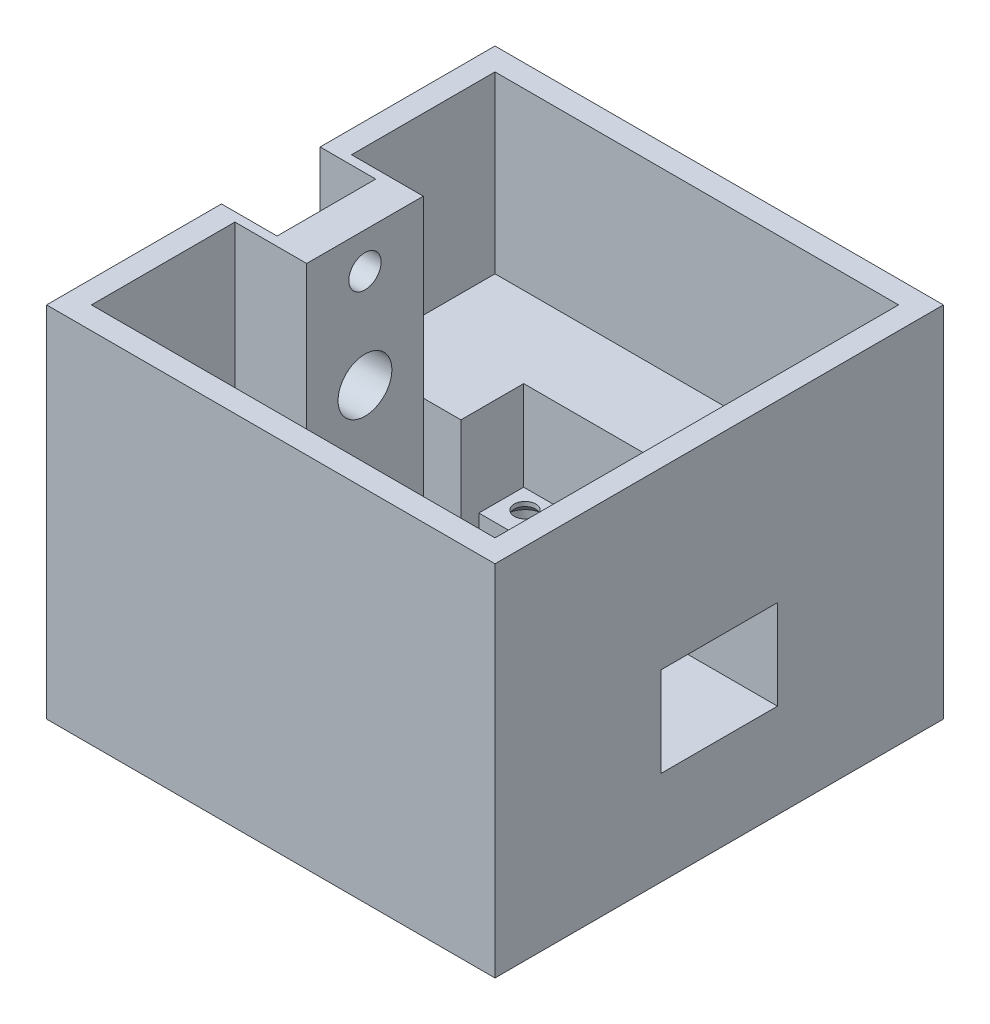
SolidWorks part; units mm, degrees
ref_plane "Front Plane" through (0, 0, 0) normal (0, 0, 1) x (1, 0, 0)
ref_plane "Top Plane" through (0, 0, 0) normal (0, 1, 0) x (1, 0, 0)
ref_plane "Right Plane" through (0, 0, 0) normal (1, 0, 0) x (0, 0, -1)
sketch "Sketch1" plane through (0, 0, 0) normal (0, 1, 0) x (1, 0, 0)
  line L1 (25, 25) -> (-25, 25)
  line L2 (25, 25) -> (25, -25)
  line L3 (25, -25) -> (-25, -25)
  line L4 (-25, 25) -> (-25, -25)
  line L5 (25, 25) -> (-25, -25) construction
  line L6 (25, -25) -> (-25, 25) construction
  point P0 (0, 0)
  dimension "D1" = 50
  dimension "D2" = 50
extrude "Boss-Extrude1" add sketch "Sketch1" along normal blind 40
shell "Shell1" thickness 2.5
sketch "Sketch2" plane through (0, 2.5, 0) normal (0, 1, 0) x (1, 0, 0)
  line L0 (9.676, 18.6496) -> (-10.324, 18.6496) construction
  line L1 (9.676, 18.6496) -> (9.676, -15.3504) construction
  line L2 (-10.3, -15.3504) -> (-10.324, -15.3504) construction
  line L3 (-10.324, 18.6496) -> (-10.324, -15.3504) construction
  line L4 (-10.3, 4.5) -> (-22.5, 4.5)
  line L5 (-22.5, 4.5) -> (-22.5, 22.5)
  line L6 (-22.5, 22.5) -> (0, 22.5)
  line L7 (-10.3, 4.5) -> (-10.3, 13.5)
  line L8 (-10.3, 13.5) -> (0, 13.5)
  line L9 (22.5, 4.5) -> (22.5, 22.5)
  line L10 (10.3, 4.5) -> (22.5, 4.5)
  line L11 (10.3, 4.5) -> (10.3, 13.5)
  line L12 (10.3, 13.5) -> (0, 13.5)
  line L13 (22.5, 22.5) -> (0, 22.5)
  line L14 (10.3, -12) -> (22.5, -12)
  line L15 (12.1528, -14.5584) -> (12.1503, -21.7784) construction
  line L16 (-22.5, -12) -> (-22.5, -22.5)
  line L17 (-10.3, -12) -> (-22.5, -12)
  line L18 (-10.3, -12) -> (-10.3, -19.19)
  line L19 (-10.3, -19.19) -> (0.1901, -19.19)
  line L20 (-22.5, -22.5) -> (2.3162, -22.5)
  line L21 (-10.324, 18.6496) -> (-10.324, 11.4396) construction
  line L22 (10.3, -12) -> (10.3, -19.19)
  line L23 (9.676, -15.3504) -> (-10.3, -15.3504) construction
  line L24 (10.3, -19.19) -> (0.1901, -19.19)
  line L25 (22.5, -22.5) -> (2.3162, -22.5)
  line L26 (22.5, -12) -> (22.5, -22.5)
  line L27 (-22.5, -22.5) -> (22.5, -22.5) construction
  line L28 (-22.5, 22.5) -> (-22.5, -22.5) construction
  line L29 (-22.5, 22.5) -> (-22.5, -22.5) construction
  line L30 (22.5, 22.5) -> (-22.5, 22.5) construction
  point P0 (2.1262, -4.7549)
  dimension "D1" = 18
  dimension "D2" = 10.5
  dimension "D3" = 9
extrude "Boss-Extrude2" [suppressed] add sketch "Sketch2" along normal blind 18
sketch "Sketch4" [suppressed] plane through (0, 2.5, 0) normal (0, 1, 0) x (1, 0, 0)
  line L0 (22.5, -12) -> (22.5, 4.5)
  line L1 (22.5, -3.75) -> (15.5, -3.75)
  line L3 (14, -2.25) -> (17, -2.25)
  line L4 (14, -2.25) -> (14, -5.25)
  line L5 (14, -5.25) -> (17, -5.25)
  line L6 (17, -2.25) -> (17, -5.25)
  line L7 (14, -2.25) -> (17, -5.25) construction
  line L8 (14, -5.25) -> (17, -2.25) construction
  dimension "D1" = 3
  dimension "D2" = 3
  dimension "D3" = 7
extrude "Cut-Extrude2" [suppressed] cut sketch "Sketch4" against normal through all
sketch "Sketch5" [suppressed] plane through (-22.5, 0, 0) normal (1, 0, 0) x (0, 0, -1)
  line L0 (4.5, 2.5) -> (-12, 2.5) construction
  line L1 (-6.75, 2.5) -> (-0.75, 2.5)
  line L2 (-6.75, 2.5) -> (-6.75, 40)
  line L3 (-6.75, 40) -> (-0.75, 40)
  line L4 (-0.75, 2.5) -> (-0.75, 40)
  line L5 (22.5, 40) -> (-22.5, 40) construction
  line L6 (-12, 2.5) -> (4.5, 2.5) construction
  point P12 (-3.75, 2.5)
  point P16 (-3.75, 2.5)
  dimension "D1" = 6
extrude "Boss-Extrude3" [suppressed] add sketch "Sketch5" along normal blind 2.5
sketch "Sketch6" [suppressed] plane through (-20, 0, 0) normal (1, 0, 0) x (0, 0, -1)
  line L0 (-6.75, 21.25) -> (-0.75, 21.25)
  line L1 (-6.75, 40) -> (-6.75, 2.5) construction
  line L2 (-0.75, 2.5) -> (-0.75, 40) construction
  line L4 (-5.5999, 21.4224) -> (-3.4786, 23.5437)
  line L5 (-5.5999, 21.4224) -> (-3.4786, 19.3011)
  line L6 (-3.4786, 19.3011) -> (-1.3573, 21.4224)
  line L7 (-3.4786, 23.5437) -> (-1.3573, 21.4224)
  line L8 (-5.2251, 22.5516) -> (-2.05, 19.75) construction
  line L9 (-5.05, 19.75) -> (-2.2784, 22.948) construction
  point P6 (-3.75, 21.25)
  dimension "D1" = 3
  dimension "D2" = 3
extrude "Cut-Extrude3" [suppressed] cut sketch "Sketch6" against normal through all contours L5 L6 L0 | L7 L4 L5 L0 L6
hole_wizard "M1.6 Tapped Hole1" [suppressed] positions "Sketch7" profile "Sketch8" tap size "M1.6" standard "ISO"
sketch "Sketch7" [suppressed] plane through (0, 12.5, 0) normal (0, 1, 0) x (1, 0, 0)
  line L0 (-10.3, 4.5) -> (-10.3, 11.5) construction
  line L1 (-22.5, 4.5) -> (-10.3, 4.5) construction
  line L2 (22.5, -12) -> (10.3, -12) construction
  line L3 (10.3, -12) -> (10.3, -19.19) construction
  point P0 (-12.3, 6.5)
  point P2 (12.3, -14)
  dimension "D1" = 2
  dimension "D2" = 2
  dimension "D3" = 2
  dimension "D4" = 2
sketch "Sketch8" plane through (-12.3, 12.5, -6.5) normal (1, 0, 0) x (0, 0, 1)
  line L0 (0, 0) -> (0, 12.5)
  line L1 (0, 12.5) -> (0.625, 12.5)
  line L2 (0.625, 12.5) -> (0.625, 0.2)
  line L3 (0.625, 0.2) -> (0.825, 0)
  line L5 (0.825, 0) -> (0, 0)
  line L6 (-0.625, 0.2) -> (-0.825, 0) construction
  line L11 (0, -6.35) -> (0, 107.95) construction
  dimension "Thru Tap Drill Dia." = 1.25
  dimension "Thru Tap Drill Depth" = 12.5
  dimension "Near C'Sink Dia." = 1.65
  dimension "Near C'Sink Angle" = 90
cosmetic thread "Hole Thread1" [suppressed] parameters "D2"=1.6
cosmetic thread "Hole Thread2" [suppressed] parameters "D2"=1.6
sketch "Sketch9" [suppressed] plane through (0, 2.5, 0) normal (0, 1, 0) x (1, 0, 0)
  line L1 (-10.3, 13.5) -> (10.3, 13.5)
  line L2 (-10.3, 13.5) -> (-10.3, -19.19)
  line L3 (-10.3, -19.19) -> (10.3, -19.19)
  line L4 (10.3, 13.5) -> (10.3, -19.19)
extrude "Boss-Extrude4" [suppressed] add sketch "Sketch9" along normal blind 8
hole_wizard "CSK SLOT for M1.6 Countersunk Flat Head Screw1" [suppressed] positions "Sketch10" profile "Sketch11" size "M1.6" standard "ISO"
sketch "Sketch10" [suppressed] plane through (0, 10.5, 0) normal (0, 1, 0) x (1, 0, 0)
  line L0 (0, 0) -> (0, 4.5)
  point P0 (0, 4.5)
  dimension "D1" = 4.5
sketch "Sketch11" plane through (0, 10.5, -4.5) normal (1, 0, 0) x (0, 0, 1)
  line L0 (0, 0) -> (0, 10.5)
  line L1 (0, 10.5) -> (0.9, 10.5)
  line L2 (0.9, 10.5) -> (0.9, 6.9)
  line L3 (0.9, 6.9) -> (1.8, 6)
  line L4 (1.8, 6) -> (1.8, 0)
  line L6 (1.8, 0) -> (0, 0)
  line L7 (-0.9, 6.9) -> (-1.8, 6) construction
  line L11 (0, -6.35) -> (0, 107.95) construction
  dimension "Thru Hole Dia." = 1.8
  dimension "Thru Hole Depth" = 10.5
  dimension "C'Sink Dia." = 3.6
  dimension "C'Sink Angle" = 90
  dimension "Head Clearance" = 6
ref_plane "Plane1" [suppressed] through (0, 10.5, 0) normal (0, 1, 0) x (1, 0, 0)
sketch "Sketch12" [suppressed] plane through (0, 10.5, 0) normal (0, 1, 0) x (1, 0, 0)
  line L0 (0, 22.5) -> (0, -22.5)
  line L1 (22.5, 22.5) -> (-22.5, 22.5) construction
  line L2 (-22.5, -22.5) -> (22.5, -22.5) construction
  point P6 (0, -11)
  point P7 (0, 11)
  point P8 (0, 0)
  dimension "D1" = 11
  dimension "D2" = 11
hole_wizard "CSK SLOT for M1.6 Countersunk Flat Head Screw2" [suppressed] positions "Sketch13" profile "Sketch14" size "M1.6" standard "ISO"
sketch "Sketch13" [suppressed] plane through (0, 10.5, 0) normal (0, 1, 0) x (1, 0, 0)
  point P0 (0, -11)
  point P3 (0, 11)
sketch "Sketch14" plane through (0, 10.5, 11) normal (1, 0, 0) x (0, 0, 1)
  line L0 (0, 0) -> (0, 10.5)
  line L1 (0, 10.5) -> (0.9, 10.5)
  line L2 (0.9, 10.5) -> (0.9, 7.9)
  line L3 (0.9, 7.9) -> (1.8, 7)
  line L4 (1.8, 7) -> (1.8, 0)
  line L6 (1.8, 0) -> (0, 0)
  line L7 (-0.9, 7.9) -> (-1.8, 7) construction
  line L11 (0, -6.35) -> (0, 107.95) construction
  dimension "Thru Hole Dia." = 1.8
  dimension "Thru Hole Depth" = 10.5
  dimension "C'Sink Dia." = 3.6
  dimension "C'Sink Angle" = 90
  dimension "Head Clearance" = 7
sketch "Sketch15" [suppressed] plane through (0, 0, 0) normal (0, -1, 0) x (1, 0, 0)
  line L0 (-25, 0) -> (25, 0)
  line L1 (-25, -25) -> (-25, 25) construction
  line L2 (25, 25) -> (25, -25) construction
  line L3 (0, -22.5) -> (0, 22.5) construction
  line L4 (-4.5, 15.5) -> (4.5, 15.5)
  line L5 (-4.5, 15.5) -> (-4.5, -15.5)
  line L6 (-4.5, -15.5) -> (4.5, -15.5)
  line L7 (4.5, 15.5) -> (4.5, -15.5)
  line L8 (-4.5, 15.5) -> (4.5, -15.5) construction
  line L9 (-4.5, -15.5) -> (4.5, 15.5) construction
  point P6 (0, 0)
  point P8 (0, 0)
  dimension "D1" = 31
  dimension "D2" = 9
extrude "Cut-Extrude4" [suppressed] cut sketch "Sketch15" against normal blind 6.1 contours L5 L6 L7 L4
sketch "Sketch16" plane through (0, 2.5, 0) normal (0, 1, 0) x (1, 0, 0)
  line L0 (9.676, 17.0496) -> (-10.324, 17.0496) construction
  line L1 (9.676, 17.0496) -> (9.676, -16.9504) construction
  line L2 (-10.3, -16.9504) -> (-10.324, -16.9504) construction
  line L3 (-10.324, 17.0496) -> (-10.324, -16.9504) construction
  line L4 (-10.3, 6.5) -> (-22.5, 6.5)
  line L5 (-22.5, 6.5) -> (-22.5, 22.5)
  line L6 (-22.5, 22.5) -> (-5.1691, 22.5)
  line L7 (-10.3, 6.5) -> (-10.3, 13.5)
  line L8 (-10.3, 13.5) -> (-5.1691, 13.5)
  line L9 (22.5, 6.5) -> (22.5, 22.5)
  line L10 (10.3, 6.5) -> (22.5, 6.5)
  line L11 (10.3, 6.5) -> (10.3, 13.5)
  line L12 (10.3, 13.5) -> (-5.1691, 13.5)
  line L13 (22.5, 22.5) -> (-5.1691, 22.5)
  line L14 (10.3, -13.6) -> (22.5, -13.6)
  line L15 (4.8575, -15.2543) -> (4.855, -22.4742) construction
  line L16 (-22.5, -13.6) -> (-22.5, -22.5)
  line L17 (-10.3, -13.6) -> (-22.5, -13.6)
  line L18 (-10.3, -13.6) -> (-10.3, -20.79)
  line L19 (-10.3, -20.79) -> (-4.9791, -20.79)
  line L20 (-22.5, -22.5) -> (-4.9791, -22.5)
  line L21 (-10.324, 17.0496) -> (-10.324, 9.8396) construction
  line L22 (10.3, -13.6) -> (10.3, -20.79)
  line L23 (9.676, -16.9504) -> (-10.3, -16.9504) construction
  line L24 (10.3, -20.79) -> (-4.9791, -20.79)
  line L25 (22.5, -22.5) -> (-4.9791, -22.5)
  line L26 (22.5, -13.6) -> (22.5, -22.5)
  line L27 (22.5, 22.5) -> (-22.5, 22.5) construction
  line L29 (22.5, -22.5) -> (22.5, 22.5) construction
  line L30 (22.5, -22.5) -> (22.5, 22.5) construction
  line L31 (-22.5, -22.5) -> (22.5, -22.5) construction
  point P0 (-5.1691, -5.4508)
  dimension "D1" = 34
  dimension "D2" = 12.2
  dimension "D3" = 16
  dimension "D4" = 8.9
  dimension "D5" = 1.71
  dimension "D6" = 12.2
  dimension "D7" = 9
  dimension "D8" = 45
  dimension "D9" = 45
extrude "Boss-Extrude5" add sketch "Sketch16" along normal blind 18
sketch "Sketch17" plane through (0, 2.5, 0) normal (0, 1, 0) x (1, 0, 0)
  line L1 (0, 22.5) -> (0, -22.5)
  line L2 (22.5, 22.5) -> (-22.5, 22.5) construction
  line L3 (-22.5, -22.5) -> (22.5, -22.5) construction
  line L4 (0, 0) -> (-22.5, 0)
  line L5 (-22.5, 6.5) -> (-22.5, -13.6) construction
  line L6 (-22.5, 22.5) -> (-22.5, -22.5) construction
  line L7 (22.5, 6.5) -> (-22.5, 6.5)
  line L8 (22.5, 6.5) -> (22.5, -6.5)
  line L9 (22.5, -6.5) -> (-22.5, -6.5)
  line L10 (-22.5, 6.5) -> (-22.5, -6.5)
  line L11 (22.5, 6.5) -> (-22.5, -6.5) construction
  line L12 (22.5, -6.5) -> (-22.5, 6.5) construction
  line L13 (-22.5, 6.5) -> (-10.3, 6.5) construction
  line M11 (22.5, -13.6) -> (22.5, 6.5)
  line M12 (22.5, 6.5) -> (10.3, 6.5)
  line M16 (-10.3, 6.5) -> (-22.5, 6.5)
  line M17 (-22.5, 6.5) -> (-22.5, -13.6)
extrude "Boss-Extrude6" add sketch "Sketch17" along normal blind 8 contours L1 L7 L4 M16 M17 | L9 L1 L4 M17 | L9 L7 L1 M11 M12
sketch "Sketch18" plane through (-22.5, 0, 0) normal (1, 0, 0) x (0, 0, -1)
  line L0 (-22.5, 40) -> (22.5, 40)
  line L1 (22.5, 40) -> (0, 40)
  line L2 (0, 40) -> (0, 10.5)
  line L3 (6.5, 10.5) -> (-6.5, 10.5) construction
  line L5 (6.5, 40) -> (-6.5, 40)
  line L6 (6.5, 40) -> (6.5, 10.5)
  line L7 (6.5, 10.5) -> (-6.5, 10.5)
  line L8 (-6.5, 40) -> (-6.5, 10.5)
  line L9 (6.5, 40) -> (-6.5, 10.5) construction
  line L10 (6.5, 10.5) -> (-6.5, 40) construction
  point P9 (0, 25.25)
  line M2 (-6.5, 10.5) -> (6.5, 10.5)
  line M3 (6.5, 10.5) -> (6.5, 20.5)
extrude "Boss-Extrude7" add sketch "Sketch18" along normal blind 8 contours L6 L1 L2 M2 M3 | L0 L8 L2 M2
sketch "Sketch19" plane through (-25, 0, 0) normal (-1, 0, 0) x (0, 0, 1)
  line L0 (-25, 40) -> (25, 40) construction
  line L2 (0, 9.8) -> (0, 0) construction
  line L3 (-5.5, 9.8) -> (5.5, 9.8)
  line L4 (-5.5, 9.8) -> (-5.5, 40)
  line L5 (-5.5, 40) -> (5.5, 40)
  line L6 (5.5, 9.8) -> (5.5, 40)
  point P5 (0, 20)
  point P7 (0, 20)
  dimension "D1" = 30.2
  dimension "D2" = 11
extrude "Cut-Extrude5" cut sketch "Sketch19" against normal blind 6.2
sketch "Sketch20" plane through (0, 0, 0) normal (0, -1, 0) x (1, 0, 0)
  line L0 (-25, 0) -> (25, 0)
  line L1 (-25, -25) -> (-25, 25) construction
  line L2 (25, 25) -> (25, -25) construction
  line L4 (15.1, 5.4) -> (-15.1, 5.4)
  line L5 (15.1, 5.4) -> (15.1, -5.4)
  line L6 (15.1, -5.4) -> (-15.1, -5.4)
  line L7 (-15.1, 5.4) -> (-15.1, -5.4)
  line L8 (15.1, 5.4) -> (-15.1, -5.4) construction
  line L9 (15.1, -5.4) -> (-15.1, 5.4) construction
  point P6 (0, 0)
  point P8 (0, 0)
  dimension "D1" = 30.2
  dimension "D2" = 10.8
extrude "Cut-Extrude6" cut sketch "Sketch20" against normal blind 6.2 contours L4 L7 L0 L5 | L0 L7 L6 L5
sketch "Sketch21" plane through (0, 2.5, 0) normal (0, 1, 0) x (1, 0, 0)
  line L0 (0, -20.79) -> (0, -11.8673) construction
  line L1 (10.3, -20.79) -> (5.3, -20.79)
  line L2 (10.3, -20.79) -> (10.3, -15.79)
  line L3 (10.3, -15.79) -> (5.3, -15.79)
  line L4 (5.3, -20.79) -> (5.3, -15.79)
  line L5 (10.3, -20.79) -> (-10.3, -20.79) construction
  line L6 (-10.3, -15.79) -> (-5.3, -15.79)
  line L7 (-5.3, -20.79) -> (-5.3, -15.79)
  line L8 (-10.3, -20.79) -> (-5.3, -20.79)
  line L9 (-10.3, -20.79) -> (-10.3, -15.79)
  dimension "D1" = 5
  dimension "D2" = 5
extrude "Boss-Extrude8" add sketch "Sketch21" along normal blind 8
sketch3d "3DSketch1"
  line L0 (-10.3, 10.5, 15.79) -> (-10.3, 10.5, 20.79) construction
  line L5 (-10.3, 10.5, 20.79) -> (-5.3, 10.5, 20.79) construction
  line L6 (10.3, 10.5, 20.79) -> (10.3, 10.5, 15.79) construction
  line L7 (5.3, 10.5, 20.79) -> (10.3, 10.5, 20.79) construction
  point P0 (-8, 10.5, 18.64)
  point P7 (8, 10.5, 18.64)
  dimension "D1" = 2.3
  dimension "D2" = 2.15
  dimension "D3" = 2.3
  dimension "D4" = 2.15
hole_wizard "CSK SLOT for M1.6 Countersunk Flat Head Screw3" [suppressed] positions "Sketch22" profile "Sketch23" size "M1.6" standard "ISO"
sketch "Sketch22" plane through (0, 0, 0) normal (0, -1, 0) x (-1, 0, 0)
  line L0 (25, -25) -> (-25, -25) construction
  line L1 (-25, -25) -> (-25, 25) construction
  line L2 (25, 25) -> (25, -25) construction
  line L3 (-25, 25) -> (25, 25) construction
  point P0 (-8, -18.64)
  point P3 (8, -18.64)
  point P19 (-8, 11.35)
  point P21 (8, 11.35)
  dimension "D1" = 6.36
  dimension "D2" = 17
  dimension "D3" = 17
  dimension "D4" = 6.36
  dimension "D5" = 17
  dimension "D6" = 17
  dimension "D7" = 13.65
  dimension "D8" = 13.65
sketch "Sketch23" plane through (8, 0, 18.64) normal (1, 0, 0) x (0, 0, -1)
  line L0 (0, 0) -> (0, 40)
  line L1 (0, 40) -> (0.9, 40)
  line L2 (0.9, 40) -> (0.9, 9.9)
  line L3 (0.9, 9.9) -> (1.8, 9)
  line L4 (1.8, 9) -> (1.8, 0)
  line L6 (1.8, 0) -> (0, 0)
  line L7 (-0.9, 9.9) -> (-1.8, 9) construction
  line L11 (0, -6.35) -> (0, 107.95) construction
  dimension "Thru Hole Dia." = 1.8
  dimension "Thru Hole Depth" = 40
  dimension "C'Sink Dia." = 3.6
  dimension "C'Sink Angle" = 90
  dimension "Head Clearance" = 9
ref_plane "Plane3" through (0, 0, 3.79) normal (0, 0, -1) x (-1, 0, 0)
mirror "Mirror1" [suppressed] about plane through (0, 0, 3.79) normal (0, 0, -1)
sketch "Sketch24" plane through (0, 10.5, 0) normal (0, 1, 0) x (1, 0, 0)
  line L0 (-25, 0) -> (25, 0) construction
  line L1 (-25, 5.5) -> (-25, -5.5) construction
  line L2 (25, -25) -> (25, 25) construction
  point P6 (-11, 0)
  point P7 (11, 0)
  point P8 (0, 0)
  dimension "D1" = 11
  dimension "D2" = 11
hole_wizard "CSK SLOT for M1.6 Countersunk Flat Head Screw4" positions "Sketch27" profile "Sketch26" size "M1.6" standard "ISO" slot yes end condition through all
sketch "Sketch27" plane through (0, 10.5, 0) normal (0, 1, 0) x (1, 0, 0)
  point P0 (-11, 0)
  point P3 (11, 0)
sketch "Sketch26" plane through (-11, 10.5, 0) normal (1, 0, 0) x (0, 0, 1)
  line L0 (0, 0) -> (0, 10.5)
  line L1 (0, 10.5) -> (0.9, 10.5)
  line L2 (0.9, 10.5) -> (0.9, 3.9)
  line L3 (0.9, 3.9) -> (1.8, 3)
  line L4 (1.8, 3) -> (1.8, 0)
  line L6 (1.8, 0) -> (0, 0)
  line L7 (-0.9, 3.9) -> (-1.8, 3) construction
  line L11 (0, -6.35) -> (0, 107.95) construction
  dimension "Thru Hole Dia." = 1.8
  dimension "Thru Hole Depth" = 10.5
  dimension "C'Sink Dia." = 3.6
  dimension "C'Sink Angle" = 90
  dimension "Head Clearance" = 3
sketch "Sketch28" plane through (0, 10.5, 0) normal (0, 1, 0) x (1, 0, 0)
  circle A0 centre (0, 0) radius 3
  dimension "D1" = 6
extrude "Cut-Extrude7" cut sketch "Sketch28" against normal through all
sketch "Sketch29" plane through (-14.5, 0, 0) normal (1, 0, 0) x (0, 0, -1)
  line L0 (0, 40) -> (0, 10.5)
  line L1 (6.5, 40) -> (-6.5, 40) construction
  line L2 (-6.5, 10.5) -> (6.5, 10.5) construction
  point P6 (0, 36)
  point P7 (0, 14)
  point P8 (0, 25)
  dimension "D1" = 15
  dimension "D2" = 11
  dimension "D3" = 11
hole_wizard "CSK SLOT for M1.6 Countersunk Flat Head Screw5" positions "Sketch30" profile "Sketch31" size "M1.6" standard "ISO" slot yes end condition through all
sketch "Sketch30" plane through (-14.5, 0, 0) normal (1, 0, 0) x (0, 0, -1)
  point P0 (0, 36)
  point P3 (0, 14)
sketch "Sketch31" plane through (-14.5, 36, 0) normal (0, 1, 0) x (0, 0, -1)
  line L0 (0, 0) -> (0, 10.5)
  line L1 (0, 10.5) -> (0.9, 10.5)
  line L2 (0.9, 10.5) -> (0.9, 3.9)
  line L3 (0.9, 3.9) -> (1.8, 3)
  line L4 (1.8, 3) -> (1.8, 0)
  line L6 (1.8, 0) -> (0, 0)
  line L7 (-0.9, 3.9) -> (-1.8, 3) construction
  line L11 (0, -6.35) -> (0, 107.95) construction
  dimension "Thru Hole Dia." = 1.8
  dimension "Thru Hole Depth" = 10.5
  dimension "C'Sink Dia." = 3.6
  dimension "C'Sink Angle" = 90
  dimension "Head Clearance" = 3
sketch "Sketch32" plane through (-14.5, 0, 0) normal (1, 0, 0) x (0, 0, -1)
  circle A0 centre (0, 25) radius 3
  dimension "D1" = 6
extrude "Cut-Extrude8" cut sketch "Sketch32" against normal through all
sketch "Sketch33" plane through (25, 0, 0) normal (1, 0, 0) x (0, 0, -1)
  circle A0 centre (0, 14) radius 4
  dimension "D1" = 8
extrude "Cut-Extrude9" [suppressed] cut sketch "Sketch33" against normal up to vertex
sketch "Sketch34" plane through (0, 10.5, 0) normal (0, 1, 0) x (1, 0, 0)
  line L0 (-3, 0) -> (-3, -6.5)
  line L1 (-25, 0) -> (25, 0) construction
  line L2 (22.5, -6.5) -> (-22.5, -6.5) construction
  line L3 (-3, -6.5) -> (3, -6.5)
  line L4 (22.5, -6.5) -> (-14.5, -6.5) construction
  line L5 (3, -6.5) -> (3, 0)
  line L6 (-3, 0) -> (3, 0)
  circle A0 centre (0, 0) radius 3 construction
extrude "Cut-Extrude10" cut sketch "Sketch34" against normal up to surface (8 mm away) up to face at (0, 2.5, 14.345)
sketch "Sketch35" plane through (0, 2.5, 0) normal (0, 1, 0) x (1, 0, 0)
  line L0 (0, 13.5) -> (0, 6.5) construction
  line L1 (-10.3, 13.5) -> (-5.3, 13.5)
  line L2 (-10.3, 13.5) -> (-10.3, 8.5)
  line L3 (-10.3, 8.5) -> (-5.3, 8.5)
  line L4 (-5.3, 13.5) -> (-5.3, 8.5)
  line L9 (-10.3, 13.5) -> (10.3, 13.5) construction
  line L10 (10.3, 6.5) -> (-10.3, 6.5) construction
  line L11 (10.3, 8.5) -> (5.3, 8.5)
  line L12 (5.3, 13.5) -> (5.3, 8.5)
  line L13 (10.3, 13.5) -> (5.3, 13.5)
  line L14 (10.3, 13.5) -> (10.3, 8.5)
  dimension "D1" = 5
  dimension "D2" = 5
extrude "Boss-Extrude9" add sketch "Sketch35" along normal blind 8
hole_wizard "CSK SLOT for M2 Countersunk Flat Head Screw1" positions "Sketch36" profile "Sketch37" size "M2" standard "ISO" slot yes end condition through all
sketch "Sketch36" plane through (0, 0, 0) normal (0, -1, 0) x (-1, 0, 0)
  line L0 (-25, -25) -> (-25, 25) construction
  line L1 (-25, 25) -> (25, 25) construction
  line L2 (25, -25) -> (-25, -25) construction
  line L3 (0, 25) -> (0, -25) construction
  point P0 (-8, -18.64)
  point P8 (-8, 11.35)
  point P21 (8, -18.64)
  point P22 (8, 11.35)
  dimension "D1" = 17
  dimension "D2" = 17
  dimension "D3" = 13.65
  dimension "D4" = 6.36
sketch "Sketch37" plane through (8, 0, 18.64) normal (1, 0, 0) x (0, 0, -1)
  line L0 (0, 0) -> (0, 40)
  line L1 (0, 40) -> (1.2, 40)
  line L2 (1.2, 40) -> (1.2, 10)
  line L3 (1.2, 10) -> (2.2, 9)
  line L4 (2.2, 9) -> (2.2, 0)
  line L6 (2.2, 0) -> (0, 0)
  line L7 (-1.2, 10) -> (-2.2, 9) construction
  line L11 (0, -6.35) -> (0, 107.95) construction
  dimension "Thru Hole Dia." = 2.4
  dimension "Thru Hole Depth" = 40
  dimension "C'Sink Dia." = 4.4
  dimension "C'Sink Angle" = 90
  dimension "Head Clearance" = 9
sketch "Sketch38" plane through (22.5, 0, 0) normal (-1, 0, 0) x (0, 0, 1)
  line L0 (6.5, 10.5) -> (6.5, 20.5)
  line L1 (6.5, 20.5) -> (-6.5, 20.5)
  line L2 (-6.5, 20.5) -> (-6.5, 10.5)
  line L3 (-6.5, 10.5) -> (6.5, 10.5)
  dimension "D1" = 10
extrude "Cut-Extrude11" cut sketch "Sketch38" against normal blind 10
